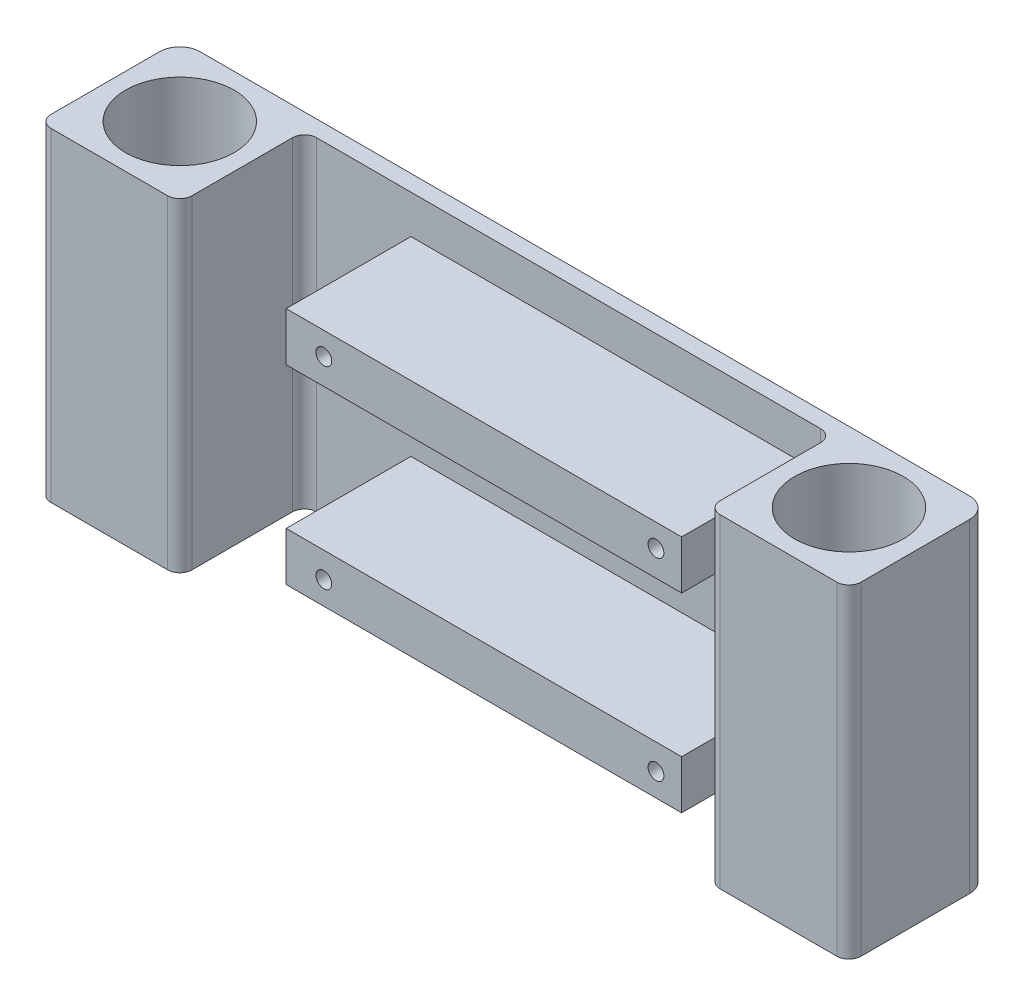
SolidWorks part; units mm, degrees
ref_plane "Front Plane" through (0, 0, 0) normal (0, 0, 1) x (1, 0, 0)
ref_plane "Top Plane" through (0, 0, 0) normal (0, 1, 0) x (1, 0, 0)
ref_plane "Right Plane" through (0, 0, 0) normal (1, 0, 0) x (0, 0, -1)
sketch "Sketch1" plane through (0, 0, 0) normal (0, 1, 0) x (1, 0, 0)
  line L1 (-17.4, 17.4) -> (17.4, 17.4)
  line L2 (-17.4, 17.4) -> (-17.4, -17.4)
  line L3 (-17.4, -17.4) -> (17.4, -17.4)
  line L4 (17.4, 13.4) -> (17.4, -17.4)
  line L5 (-17.4, 17.4) -> (17.4, -17.4) construction
  line L6 (-17.4, -17.4) -> (17.4, 17.4) construction
  line L11 (17.4, 17.4) -> (82.6, 17.4)
  line L13 (17.4, 13.4) -> (82.6, 13.4)
  line L14 (82.6, 17.4) -> (82.6, 13.4)
  circle A0 centre (0, 0) radius 13.4
  dimension "D1" = 26.8
  dimension "D2" = 34.8
  dimension "D3" = 34.8
extrude "Boss-Extrude1" add sketch "Sketch1" along normal blind 80 contours L14 L11 L4 L13 | L4 L1 L2 L3 A0
mirror "Mirror3" about plane through (82.6, 80, 0) normal (1, 0, 0) of "Boss-Extrude1"
fillet "Fillet1" radius 5 2 edges at (182.6, 40, -17.4) (-17.4, 40, -17.4)
fillet "Fillet2" radius 3 4 edges at (182.6, 40, 17.4) (147.8, 40, 17.4) (17.4, 40, 17.4) (-17.4, 40, 17.4)
sketch "Sketch2" plane through (0, 0, -13.4) normal (0, 0, 1) x (1, 0, 0)
  line L0 (17.4, 0) -> (147.8, 0) construction
  line L1 (141.2855, 11.5) -> (43.6594, 11.5)
  line L2 (141.2855, 11.5) -> (141.2855, 23.5)
  line L3 (141.2855, 23.5) -> (43.6594, 23.5)
  line L4 (43.6594, 11.5) -> (43.6594, 23.5)
  line L5 (141.2855, 58.5) -> (43.6594, 58.5)
  line L6 (141.2855, 58.5) -> (141.2855, 70.5)
  line L7 (141.2855, 70.5) -> (43.6594, 70.5)
  line L8 (43.6594, 58.5) -> (43.6594, 70.5)
  line L9 (17.4, 80) -> (147.8, 80) construction
  circle A0 centre (52.9555, 17.1906) radius 1.95
  circle A1 centre (52.9555, 64.8906) radius 1.95
  circle A2 centre (134.9555, 17.1906) radius 1.95
  circle A3 centre (134.9555, 64.8906) radius 1.95
  point P16 (0, 0)
  point P17 (0, 0)
  point P22 (0, 0)
  point P23 (0, 0)
  point P24 (0, 0)
  point P25 (130.5952, 65.0786)
  point P26 (132.9262, 17.3351)
  point P27 (134.9555, 17.1906)
  dimension "D1" = 3.9
  dimension "D2" = 3.9
  dimension "D3" = 3.9
  dimension "D4" = 3.9
  dimension "D5" = 47.7
  dimension "D6" = 11.5
  dimension "D7" = 9.5
  dimension "D8" = 12
  dimension "D9" = 12
  dimension "D10" = 82
fillet "Fillet3" radius 3 2 edges at (17.4, 40, -13.4) (147.8, 40, -13.4)
extrude "Boss-Extrude2" add sketch "Sketch2" along normal up to surface (30.8 mm away) up to face at (165.2, 40, 17.4)
